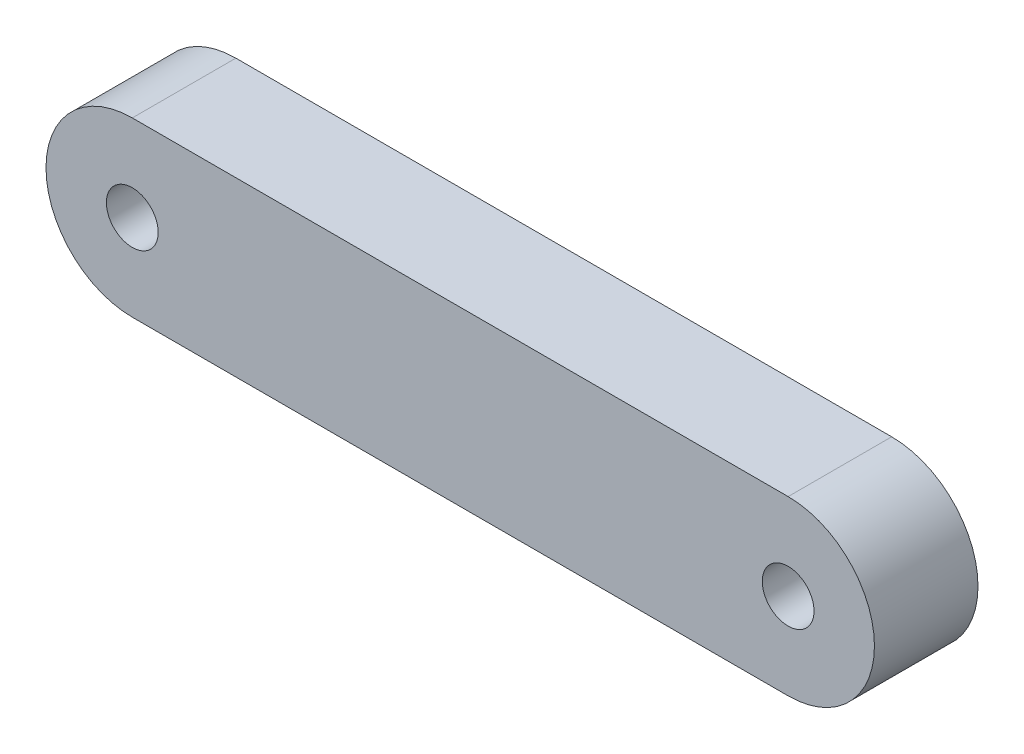
SolidWorks part; units mm, degrees
material "Acrylic (Medium-high impact)"
ref_plane "Front Plane" through (0, 0, 0) normal (0, 0, 1) x (1, 0, 0)
ref_plane "Top Plane" through (0, 0, 0) normal (0, 1, 0) x (1, 0, 0)
ref_plane "Right Plane" through (0, 0, 0) normal (1, 0, 0) x (0, 0, -1)
ref_plane "Plane1"
sketch "Sketch1" plane through (0, 0, 0) normal (0, 0, 1) x (1, 0, 0)
  line L0 (0, -5) -> (38, -5)
  line L1 (38, 5) -> (0, 5)
  arc A0 (38, -5) -> (38, 5) centre (38, 0) ccw
  arc A1 (0, 5) -> (0, -5) centre (0, 0) ccw
  circle A2 centre (0, 0) radius 1.5
  circle A3 centre (38, 0) radius 1.5
  dimension "D2" = 3
  dimension "D1" = 10
  dimension "D3" = 38
extrude "Extrusion1" add sketch "Sketch1" along normal blind 6 contours L1 A1 L0 A0 A3 A2
